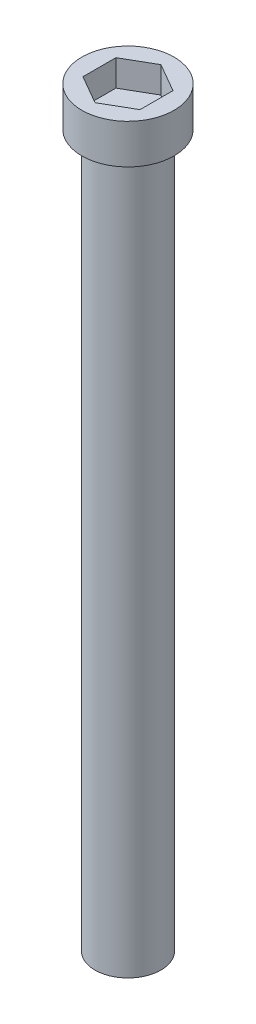
SolidWorks part; units mm, degrees
material "Cast Alloy Steel"
ref_plane "Front Plane" through (0, 0, 0) normal (0, 0, 1) x (1, 0, 0)
ref_plane "Top Plane" through (0, 0, 0) normal (0, 1, 0) x (1, 0, 0)
ref_plane "Right Plane" through (0, 0, 0) normal (1, 0, 0) x (0, 0, -1)
sketch "Sketch1" plane through (0, 0, 0) normal (0, 1, 0) x (1, 0, 0)
  circle A0 centre (0, 0) radius 2.5
  dimension "D1" = 5
extrude "Screw Length" add sketch "Sketch1" along normal blind 54
sketch "Sketch2" plane through (0, 54, 0) normal (0, 1, 0) x (1, 0, 0)
  circle A0 centre (0, 0) radius 3.5
  dimension "D1" = 7
extrude "Screw Cap" add sketch "Sketch2" along normal blind 3
sketch "Sketch3" plane through (0, 57, 0) normal (0, 1, 0) x (1, 0, 0)
  line L1 (0, 2.5) -> (-2.1651, 1.25)
  line L2 (-2.1651, 1.25) -> (-2.1651, -1.25)
  line L3 (-2.1651, -1.25) -> (0, -2.5)
  line L4 (0, -2.5) -> (2.1651, -1.25)
  line L5 (2.1651, -1.25) -> (2.1651, 1.25)
  line L6 (2.1651, 1.25) -> (0, 2.5)
  circle A0 centre (0, 0) radius 2.1651 construction
  dimension "D1" = 2.5
extrude "Screw Hole" cut sketch "Sketch3" against normal blind 2
